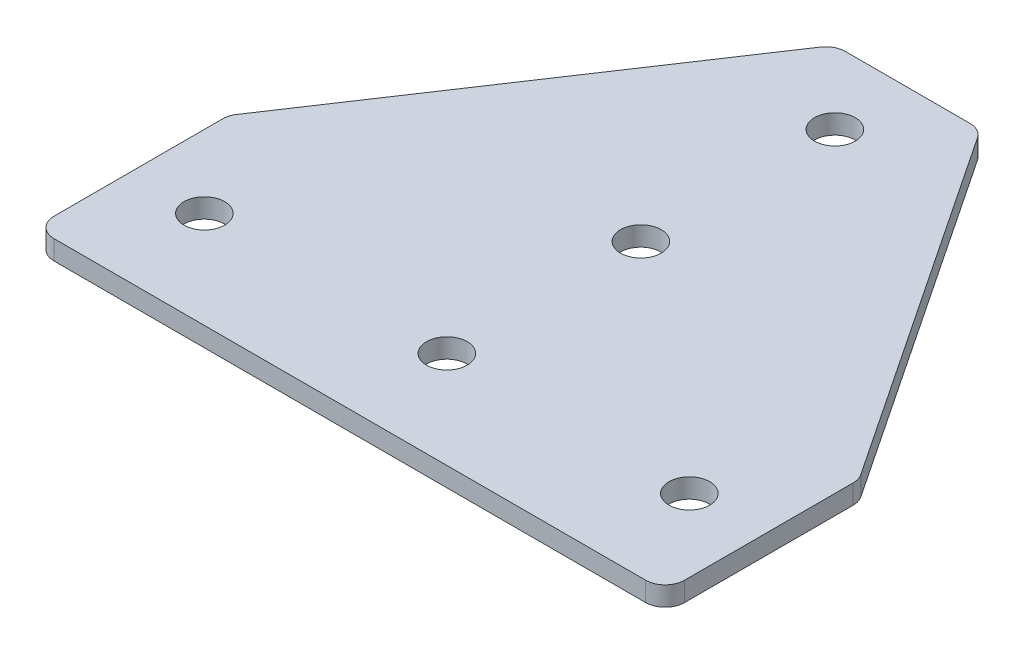
SolidWorks part; units mm, degrees
material "5052-H34"
ref_plane "正面" through (0, 0, 0) normal (0, 0, 1) x (1, 0, 0)
ref_plane "平面" through (0, 0, 0) normal (0, 1, 0) x (1, 0, 0)
ref_plane "右側面" through (0, 0, 0) normal (1, 0, 0) x (0, 0, -1)
sketch "ｽｹｯﾁ1" plane through (0, 0, 0) normal (0, 1, 0) x (1, 0, 0)
  line L0 (0, 0) -> (65, 0)
  line L1 (65, 0) -> (65, 20)
  line L2 (65, 20) -> (40, 57.5)
  line L3 (40, 57.5) -> (25, 57.5)
  line L4 (25, 57.5) -> (0, 20)
  line L5 (0, 20) -> (0, 0)
  line L6 (32.5, 0) -> (32.5, 57.5) construction
  line L7 (65, 10) -> (0, 10) construction
  circle A0 centre (7.5, 10) radius 2.1
  circle A1 centre (57.5, 10) radius 2.1
  circle A2 centre (32.5, 10) radius 2.1
  circle A3 centre (32.5, 50) radius 2.1
  circle A6 centre (32.5, 30) radius 2.1
  dimension "D3" = 4.2
  dimension "D4" = 7.5
  dimension "D5" = 7.5
  dimension "D6" = 10
  dimension "D7" = 25
  dimension "D9" = 20
  dimension "D1" = 20
  dimension "D2" = 15
extrude "ﾎﾞｽ - 押し出し1" add sketch "ｽｹｯﾁ1" along normal blind 2
fillet "ﾌｨﾚｯﾄ1" radius 2 6 edges at (0, 1, -20) (0, 1, 0) (65, 1, 0) (65, 1, -20) (40, 1, -57.5) (25, 1, -57.5)
